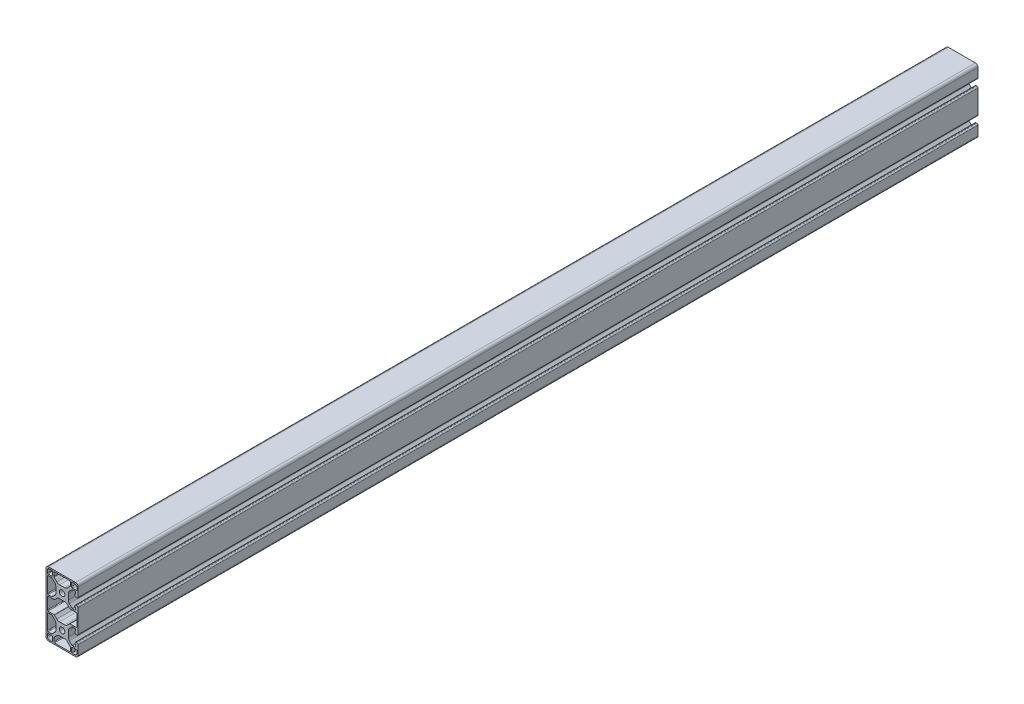
SolidWorks part; units mm, degrees
ref_plane "Front Plane" through (0, 0, 0) normal (0, 0, 1) x (1, 0, 0)
ref_plane "Top Plane" through (0, 0, 0) normal (0, 1, 0) x (1, 0, 0)
ref_plane "Right Plane" through (0, 0, 0) normal (1, 0, 0) x (0, 0, -1)
ref_plane "Plane1" through (0, 0, -4000) normal (0, 0, -1) x (-1, 0, 0)
sketch "Sketch1" plane through (0, 0, -4000) normal (0, 0, -1) x (-1, 0, 0)
  line L0 (18.3499, 55.5501) -> (18.3499, 52.5701)
  line L1 (17.7199, 51.9401) -> (13.2099, 51.9401)
  line L2 (11.9399, 53.2101) -> (11.9399, 57.7201)
  line L3 (12.5699, 58.3501) -> (15.5499, 58.3501)
  line L4 (18.3499, -12.5701) -> (18.3499, -15.5501)
  line L5 (15.5499, -18.3501) -> (12.5699, -18.3501)
  line L6 (11.9399, -17.7201) -> (11.9399, -13.2101)
  line L7 (13.2099, -11.9401) -> (17.7199, -11.9401)
  line L8 (18.3492, 27.1761) -> (18.3492, 12.8239)
  line L9 (17.4603, 11.935) -> (9.9702, 11.935)
  line L10 (9.3409, 11.6743) -> (6.5812, 8.9146)
  line L11 (3.2224, 7.5234) -> (-3.2224, 7.5234)
  line L12 (-6.5812, 8.9146) -> (-9.3409, 11.6743)
  line L13 (-9.9702, 11.935) -> (-17.4603, 11.935)
  line L14 (-18.3492, 12.8239) -> (-18.3492, 27.1761)
  line L15 (-17.4603, 28.065) -> (-9.9702, 28.065)
  line L16 (-9.3409, 28.3257) -> (-6.5812, 31.0854)
  line L17 (-3.2224, 32.4766) -> (3.2224, 32.4766)
  line L18 (6.5812, 31.0854) -> (9.3409, 28.3257)
  line L19 (9.9702, 28.065) -> (17.4603, 28.065)
  line L20 (18.3492, 9.3961) -> (18.3492, -9.3961)
  line L21 (17.4603, -10.285) -> (12.9871, -10.285)
  line L22 (12.3578, -10.0243) -> (9.0912, -6.7578)
  line L23 (7.7, -3.399) -> (7.7, 3.399)
  line L24 (9.0912, 6.7578) -> (12.3578, 10.0243)
  line L25 (12.9871, 10.285) -> (17.4603, 10.285)
  line L26 (18.3492, 49.3961) -> (18.3492, 30.6039)
  line L27 (17.4603, 29.715) -> (12.9871, 29.715)
  line L28 (12.3578, 29.9757) -> (9.0912, 33.2422)
  line L29 (7.7, 36.601) -> (7.7, 43.399)
  line L30 (9.0912, 46.7578) -> (12.3578, 50.0243)
  line L31 (12.9871, 50.285) -> (17.4603, 50.285)
  line L32 (10.2899, 57.4612) -> (10.2899, 52.992)
  line L33 (10.0292, 52.3627) -> (6.5812, 48.9146)
  line L34 (3.2224, 47.5234) -> (-3.2224, 47.5234)
  line L35 (-6.5812, 48.9146) -> (-10.0292, 52.3627)
  line L36 (-10.2899, 52.992) -> (-10.2899, 57.4612)
  line L37 (-9.401, 58.3501) -> (9.401, 58.3501)
  line L38 (10.2899, -12.992) -> (10.2899, -17.4216)
  line L39 (9.401, -18.3105) -> (-9.401, -18.3105)
  line L40 (-10.2899, -17.4216) -> (-10.2899, -12.992)
  line L41 (-10.0292, -12.3627) -> (-6.5812, -8.9146)
  line L42 (-3.2224, -7.5234) -> (3.2224, -7.5234)
  line L43 (6.5812, -8.9146) -> (10.0292, -12.3627)
  line L44 (-11.9399, 57.7201) -> (-11.9399, 53.2101)
  line L45 (-13.2099, 51.9401) -> (-17.7199, 51.9401)
  line L46 (-18.3499, 52.5701) -> (-18.3499, 55.5501)
  line L47 (-15.5499, 58.3501) -> (-12.5699, 58.3501)
  line L48 (-11.9399, -13.2101) -> (-11.9399, -17.7201)
  line L49 (-12.5699, -18.3501) -> (-15.5499, -18.3501)
  line L50 (-18.3499, -15.5501) -> (-18.3499, -12.5701)
  line L51 (-17.7199, -11.9401) -> (-13.2099, -11.9401)
  line L52 (20, -16.83) -> (20, 56.83)
  line L53 (16.83, 60) -> (-16.83, 60)
  line L54 (-20, 56.83) -> (-20, 45.5403)
  line L55 (-18.5197, 44.06) -> (-17.8048, 44.06)
  line L56 (-15.94, 45.9248) -> (-15.94, 47.2807)
  line L57 (-15.94, 47.2807) -> (-16.7, 47.2807)
  line L58 (-16.7, 47.2807) -> (-16.7, 48.9483)
  line L59 (-15.3633, 50.285) -> (-12.9871, 50.285)
  line L60 (-12.3578, 50.0243) -> (-9.0912, 46.7578)
  line L61 (-7.7, 43.399) -> (-7.7, 36.601)
  line L62 (-9.0912, 33.2422) -> (-12.3578, 29.9757)
  line L63 (-12.9871, 29.715) -> (-15.3633, 29.715)
  line L64 (-16.7, 31.0517) -> (-16.7, 32.7193)
  line L65 (-16.7, 32.7193) -> (-15.94, 32.7193)
  line L66 (-15.94, 32.7193) -> (-15.94, 34.0752)
  line L67 (-17.8048, 35.94) -> (-18.5197, 35.94)
  line L68 (-20, 34.4597) -> (-20, 5.5403)
  line L69 (-18.5197, 4.06) -> (-17.8048, 4.06)
  line L70 (-15.94, 5.9248) -> (-15.94, 7.2807)
  line L71 (-15.94, 7.2807) -> (-16.7, 7.2807)
  line L72 (-16.7, 7.2807) -> (-16.7, 9.015)
  line L73 (-15.43, 10.285) -> (-12.9871, 10.285)
  line L74 (-12.3578, 10.0243) -> (-9.0912, 6.7578)
  line L75 (-7.7, 3.399) -> (-7.7, -3.399)
  line L76 (-9.0912, -6.7578) -> (-12.3578, -10.0243)
  line L77 (-12.9871, -10.285) -> (-15.3633, -10.285)
  line L78 (-16.7, -8.9483) -> (-16.7, -7.2807)
  line L79 (-16.7, -7.2807) -> (-15.94, -7.2807)
  line L80 (-15.94, -7.2807) -> (-15.94, -5.9248)
  line L81 (-17.8048, -4.06) -> (-18.5197, -4.06)
  line L82 (-20, -5.5403) -> (-20, -16.83)
  line L83 (-16.83, -20) -> (16.83, -20)
  arc A0 (15.5499, 58.3501) -> (18.3499, 55.5501) centre (15.5499, 55.5501) cw
  arc A1 (18.3499, 52.5701) -> (17.7199, 51.9401) centre (17.7199, 52.5701) cw
  arc A2 (13.2099, 51.9401) -> (11.9399, 53.2101) centre (13.2099, 53.2101) cw
  arc A3 (11.9399, 57.7201) -> (12.5699, 58.3501) centre (12.5699, 57.7201) cw
  arc A4 (18.3499, -15.5501) -> (15.5499, -18.3501) centre (15.5499, -15.5501) cw
  arc A5 (12.5699, -18.3501) -> (11.9399, -17.7201) centre (12.5699, -17.7201) cw
  arc A6 (11.9399, -13.2101) -> (13.2099, -11.9401) centre (13.2099, -13.2101) cw
  arc A7 (17.7199, -11.9401) -> (18.3499, -12.5701) centre (17.7199, -12.5701) cw
  arc A8 (18.3492, 12.8239) -> (17.4603, 11.935) centre (17.4603, 12.8239) cw
  arc A9 (9.9702, 11.935) -> (9.3409, 11.6743) centre (9.9702, 11.045) ccw
  arc A10 (6.5812, 8.9146) -> (3.2224, 7.5234) centre (3.2224, 12.2734) cw
  arc A11 (-3.2224, 7.5234) -> (-6.5812, 8.9146) centre (-3.2224, 12.2734) cw
  arc A12 (-9.3409, 11.6743) -> (-9.9702, 11.935) centre (-9.9702, 11.045) ccw
  arc A13 (-17.4603, 11.935) -> (-18.3492, 12.8239) centre (-17.4603, 12.8239) cw
  arc A14 (-18.3492, 27.1761) -> (-17.4603, 28.065) centre (-17.4603, 27.1761) cw
  arc A15 (-9.9702, 28.065) -> (-9.3409, 28.3257) centre (-9.9702, 28.955) ccw
  arc A16 (-6.5812, 31.0854) -> (-3.2224, 32.4766) centre (-3.2224, 27.7266) cw
  arc A17 (3.2224, 32.4766) -> (6.5812, 31.0854) centre (3.2224, 27.7266) cw
  arc A18 (9.3409, 28.3257) -> (9.9702, 28.065) centre (9.9702, 28.955) ccw
  arc A19 (17.4603, 28.065) -> (18.3492, 27.1761) centre (17.4603, 27.1761) cw
  arc A20 (18.3492, -9.3961) -> (17.4603, -10.285) centre (17.4603, -9.3961) cw
  arc A21 (12.9871, -10.285) -> (12.3578, -10.0243) centre (12.9871, -9.395) cw
  arc A22 (9.0912, -6.7578) -> (7.7, -3.399) centre (12.45, -3.399) cw
  arc A23 (7.7, 3.399) -> (9.0912, 6.7578) centre (12.45, 3.399) cw
  arc A24 (12.3578, 10.0243) -> (12.9871, 10.285) centre (12.9871, 9.395) cw
  arc A25 (17.4603, 10.285) -> (18.3492, 9.3961) centre (17.4603, 9.3961) cw
  arc A26 (18.3492, 30.6039) -> (17.4603, 29.715) centre (17.4603, 30.6039) cw
  arc A27 (12.9871, 29.715) -> (12.3578, 29.9757) centre (12.9871, 30.605) cw
  arc A28 (9.0912, 33.2422) -> (7.7, 36.601) centre (12.45, 36.601) cw
  arc A29 (7.7, 43.399) -> (9.0912, 46.7578) centre (12.45, 43.399) cw
  arc A30 (12.3578, 50.0243) -> (12.9871, 50.285) centre (12.9871, 49.395) cw
  arc A31 (17.4603, 50.285) -> (18.3492, 49.3961) centre (17.4603, 49.3961) cw
  arc A32 (10.2899, 52.992) -> (10.0292, 52.3627) centre (9.3999, 52.992) cw
  arc A33 (6.5812, 48.9146) -> (3.2224, 47.5234) centre (3.2224, 52.2734) cw
  arc A34 (-3.2224, 47.5234) -> (-6.5812, 48.9146) centre (-3.2224, 52.2734) cw
  arc A35 (-10.0292, 52.3627) -> (-10.2899, 52.992) centre (-9.3999, 52.992) cw
  arc A36 (-10.2899, 57.4612) -> (-9.401, 58.3501) centre (-9.401, 57.4612) cw
  arc A37 (9.401, 58.3501) -> (10.2899, 57.4612) centre (9.401, 57.4612) cw
  arc A38 (10.0292, -12.3627) -> (10.2899, -12.992) centre (9.3999, -12.992) cw
  arc A39 (10.2899, -17.4216) -> (9.401, -18.3105) centre (9.401, -17.4216) cw
  arc A40 (-9.401, -18.3105) -> (-10.2899, -17.4216) centre (-9.401, -17.4216) cw
  arc A41 (-10.2899, -12.992) -> (-10.0292, -12.3627) centre (-9.3999, -12.992) cw
  arc A42 (-6.5812, -8.9146) -> (-3.2224, -7.5234) centre (-3.2224, -12.2734) cw
  arc A43 (3.2224, -7.5234) -> (6.5812, -8.9146) centre (3.2224, -12.2734) cw
  circle A44 centre (0, 40) radius 3.405
  circle A45 centre (0, 0) radius 3.405
  arc A46 (-11.9399, 53.2101) -> (-13.2099, 51.9401) centre (-13.2099, 53.2101) cw
  arc A47 (-17.7199, 51.9401) -> (-18.3499, 52.5701) centre (-17.7199, 52.5701) cw
  arc A48 (-18.3499, 55.5501) -> (-15.5499, 58.3501) centre (-15.5499, 55.5501) cw
  arc A49 (-12.5699, 58.3501) -> (-11.9399, 57.7201) centre (-12.5699, 57.7201) cw
  arc A50 (-13.2099, -11.9401) -> (-11.9399, -13.2101) centre (-13.2099, -13.2101) cw
  arc A51 (-11.9399, -17.7201) -> (-12.5699, -18.3501) centre (-12.5699, -17.7201) cw
  arc A52 (-15.5499, -18.3501) -> (-18.3499, -15.5501) centre (-15.5499, -15.5501) cw
  arc A53 (-18.3499, -12.5701) -> (-17.7199, -11.9401) centre (-17.7199, -12.5701) cw
  arc A54 (20, 56.83) -> (16.83, 60) centre (16.83, 56.83) ccw
  arc A55 (-16.83, 60) -> (-20, 56.83) centre (-16.83, 56.83) ccw
  arc A56 (-20, 45.5403) -> (-18.5197, 44.06) centre (-18.5197, 45.5403) ccw
  arc A57 (-17.8048, 44.06) -> (-15.94, 45.9248) centre (-17.8048, 45.9248) ccw
  arc A58 (-16.7, 48.9483) -> (-15.3633, 50.285) centre (-15.3633, 48.9483) cw
  arc A59 (-12.9871, 50.285) -> (-12.3578, 50.0243) centre (-12.9871, 49.395) cw
  arc A60 (-9.0912, 46.7578) -> (-7.7, 43.399) centre (-12.45, 43.399) cw
  arc A61 (-7.7, 36.601) -> (-9.0912, 33.2422) centre (-12.45, 36.601) cw
  arc A62 (-12.3578, 29.9757) -> (-12.9871, 29.715) centre (-12.9871, 30.605) cw
  arc A63 (-15.3633, 29.715) -> (-16.7, 31.0517) centre (-15.3633, 31.0517) cw
  arc A64 (-15.94, 34.0752) -> (-17.8048, 35.94) centre (-17.8048, 34.0752) ccw
  arc A65 (-18.5197, 35.94) -> (-20, 34.4597) centre (-18.5197, 34.4597) ccw
  arc A66 (-20, 5.5403) -> (-18.5197, 4.06) centre (-18.5197, 5.5403) ccw
  arc A67 (-17.8048, 4.06) -> (-15.94, 5.9248) centre (-17.8048, 5.9248) ccw
  arc A68 (-16.7, 9.015) -> (-15.43, 10.285) centre (-15.43, 9.015) cw
  arc A69 (-12.9871, 10.285) -> (-12.3578, 10.0243) centre (-12.9871, 9.395) cw
  arc A70 (-9.0912, 6.7578) -> (-7.7, 3.399) centre (-12.45, 3.399) cw
  arc A71 (-7.7, -3.399) -> (-9.0912, -6.7578) centre (-12.45, -3.399) cw
  arc A72 (-12.3578, -10.0243) -> (-12.9871, -10.285) centre (-12.9871, -9.395) cw
  arc A73 (-15.3633, -10.285) -> (-16.7, -8.9483) centre (-15.3633, -8.9483) cw
  arc A74 (-15.94, -5.9248) -> (-17.8048, -4.06) centre (-17.8048, -5.9248) ccw
  arc A75 (-18.5197, -4.06) -> (-20, -5.5403) centre (-18.5197, -5.5403) ccw
  arc A76 (-20, -16.83) -> (-16.83, -20) centre (-16.83, -16.83) ccw
  arc A77 (16.83, -20) -> (20, -16.83) centre (16.83, -16.83) ccw
extrude "Boss-Extrude1" add sketch "Sketch1" against normal blind 1120
